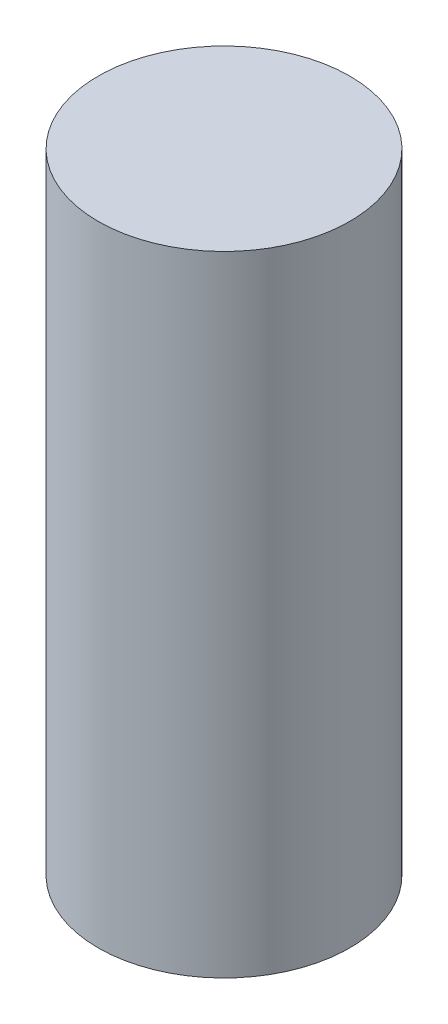
SolidWorks part; units mm, degrees
ref_plane "Front Plane" through (0, 0, 0) normal (0, 0, 1) x (1, 0, 0)
ref_plane "Top Plane" through (0, 0, 0) normal (0, 1, 0) x (1, 0, 0)
ref_plane "Right Plane" through (0, 0, 0) normal (1, 0, 0) x (0, 0, -1)
sketch "Sketch1" plane through (0, 0, 0) normal (0, 1, 0) x (1, 0, 0)
  circle A0 centre (0, 0) radius 63.5
  dimension "D1" = 127
extrude "Boss-Extrude1" add sketch "Sketch1" along normal blind 317.5
